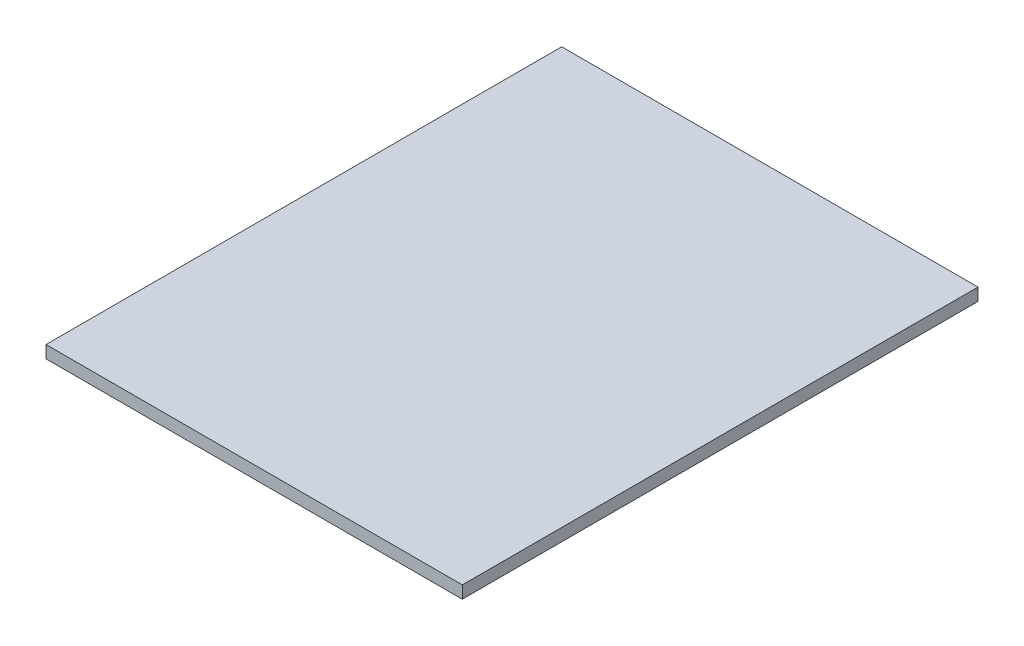
SolidWorks part; units mm, degrees
ref_plane "前视基准面" through (0, 0, 0) normal (0, 0, 1) x (1, 0, 0)
ref_plane "上视基准面" through (0, 0, 0) normal (0, 1, 0) x (1, 0, 0)
ref_plane "右视基准面" through (0, 0, 0) normal (1, 0, 0) x (0, 0, -1)
other "Configuration Table"
sketch "Sketch1" plane through (0, 0, 0) normal (0, 1, 0) x (1, 0, 0)
  line L1 (33.5, -41.5) -> (-33.5, -41.5)
  line L2 (33.5, -41.5) -> (33.5, 41.5)
  line L3 (33.5, 41.5) -> (-33.5, 41.5)
  line L4 (-33.5, -41.5) -> (-33.5, 41.5)
  line L5 (33.5, -41.5) -> (-33.5, 41.5) construction
  line L6 (33.5, 41.5) -> (-33.5, -41.5) construction
  point P0 (0, 0)
  dimension "D1" = 67
  dimension "D2" = 83
extrude "Boss-Extrude1" add sketch "Sketch1" along normal blind 2
